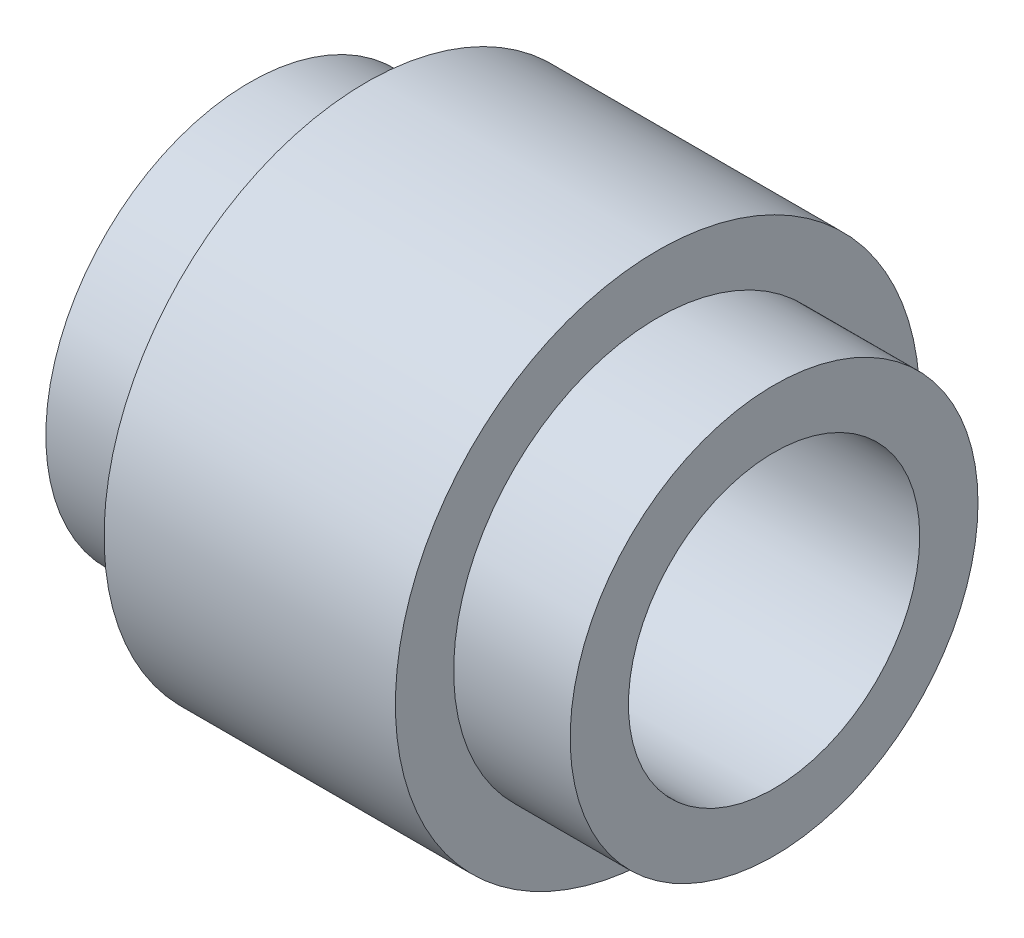
SolidWorks part; units mm, degrees
ref_plane "Front Plane" through (0, 0, 0) normal (0, 0, 1) x (1, 0, 0)
ref_plane "Top Plane" through (0, 0, 0) normal (0, 1, 0) x (1, 0, 0)
ref_plane "Right Plane" through (0, 0, 0) normal (1, 0, 0) x (0, 0, -1)
sketch "Sketch1" plane through (0, 0, 0) normal (1, 0, 0) x (0, 0, -1)
  circle A0 centre (0, 0) radius 114.3
  circle A1 centre (0, 0) radius 63.5
  dimension "D1" = 228.6
  dimension "D2" = 127
extrude "Boss-Extrude1" add sketch "Sketch1" along normal mid plane 127
sketch "Sketch2" plane through (63.5, 0, 0) normal (1, 0, 0) x (0, 0, -1)
  circle A0 centre (0, 0) radius 63.5 construction
  circle A1 centre (0, 0) radius 63.5
  circle A2 centre (0, 0) radius 88.9
  dimension "D1" = 177.8
extrude "Boss-Extrude2" add sketch "Sketch2" along normal blind 50.8
mirror "Mirror1" about plane through (0, 0, 0) normal (1, 0, 0) of "Boss-Extrude2"
